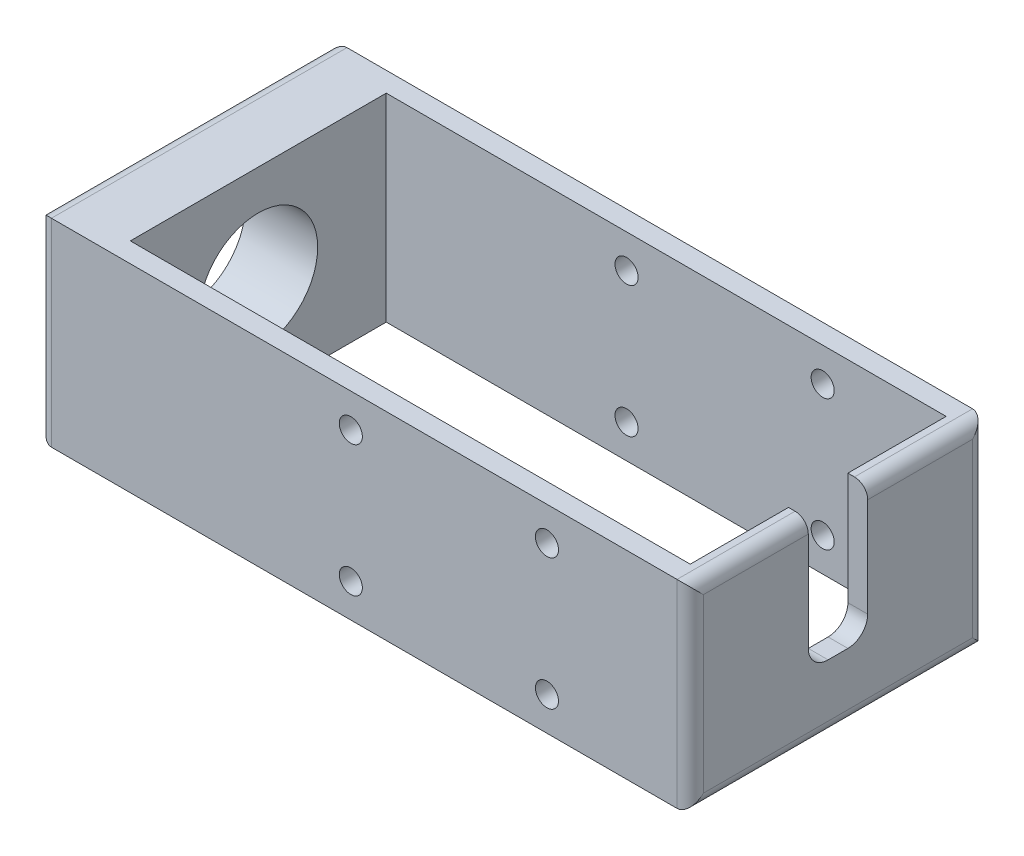
SolidWorks part; units mm, degrees
ref_plane "Front Plane" through (0, 0, 0) normal (0, 0, 1) x (1, 0, 0)
ref_plane "Top Plane" through (0, 0, 0) normal (0, 1, 0) x (1, 0, 0)
ref_plane "Right Plane" through (0, 0, 0) normal (1, 0, 0) x (0, 0, -1)
sketch "Sketch1" plane through (0, 0, 0) normal (0, 1, 0) x (1, 0, 0)
  line L1 (0, 0) -> (98.79, 0)
  line L2 (0, 0) -> (0, 44.78)
  line L3 (0, 44.78) -> (98.79, 44.78)
  line L4 (98.79, 0) -> (98.79, 44.78)
  dimension "D1" = 44.78
  dimension "D2" = 98.79
extrude "Boss-Extrude1" add sketch "Sketch1" along normal blind 30.05
shell "Shell1" thickness 3
sketch "Sketch2" plane through (0, 0, 0) normal (0, 0, 1) x (1, 0, 0)
  line L0 (98.79, 30.05) -> (98.79, 0) construction
  line L1 (0, 30.05) -> (98.79, 30.05) construction
  line L6 (0, 0) -> (98.79, 0) construction
  circle A0 centre (77.08, 24.95) radius 1.75
  circle A1 centre (77.08, 5.1) radius 1.75
  circle A2 centre (47.36, 5.1) radius 1.75
  circle A3 centre (47.36, 24.95) radius 1.75
  dimension "D1" = 21.71
  dimension "D2" = 5.1
  dimension "D3" = 3.5
  dimension "D4" = 3.5
  dimension "D5" = 21.71
  dimension "D6" = 5.1
  dimension "D7" = 3.5
  dimension "D8" = 3.5
  dimension "D9" = 29.72
  dimension "D10" = 29.72
extrude "Cut-Extrude1" cut sketch "Sketch2" against normal through all
fillet "Fillet1" radius 2 8 edges at (0, 15.025, -44.78) (0, 30.05, -22.39) (0, 15.025, 0) (0, 0, -22.39) (98.79, 15.025, 0) (98.79, 30.05, -22.39) (98.79, 15.025, -44.78) (98.79, 0, -22.39)
sketch "Sketch4" plane through (98.79, 0, 0) normal (1, 0, 0) x (0, 0, -1)
  line L0 (22.39, 30.05) -> (22.39, 0) construction
  line L1 (0, 30.05) -> (44.78, 30.05) construction
  line L2 (44.78, 0) -> (0, 0) construction
  line L4 (17.89, 30.05) -> (26.89, 30.05)
  line L5 (17.89, 30.05) -> (17.89, 13.05)
  line L6 (20.89, 10.05) -> (23.89, 10.05)
  line L7 (26.89, 30.05) -> (26.89, 13.05)
  arc A0 (23.89, 10.05) -> (26.89, 13.05) centre (23.89, 13.05) ccw
  arc A1 (20.89, 10.05) -> (17.89, 13.05) centre (20.89, 13.05) cw
  point P12 (26.89, 10.05)
  point P15 (17.89, 10.05)
  dimension "D4" = 3
  dimension "D1" = 9
  dimension "D2" = 4.5
  dimension "D3" = 20
extrude "Cut-Extrude3" cut sketch "Sketch4" against normal blind 29.61
sketch "Sketch5" plane through (0, 0, 0) normal (-1, 0, 0) x (0, 0, 1)
  line L0 (-44.78, 15.025) -> (0, 15.025) construction
  line L1 (-44.78, 30.05) -> (-44.78, 0) construction
  line L2 (0, 30.05) -> (0, 0) construction
  line L3 (-22.39, 30.05) -> (-22.39, 0) construction
  line L4 (-44.78, 30.05) -> (0, 30.05) construction
  line L5 (-44.78, 0) -> (0, 0) construction
  circle A0 centre (-22.39, 15.025) radius 9
  dimension "D1" = 18
extrude "Cut-Extrude4" cut sketch "Sketch5" against normal blind 20
